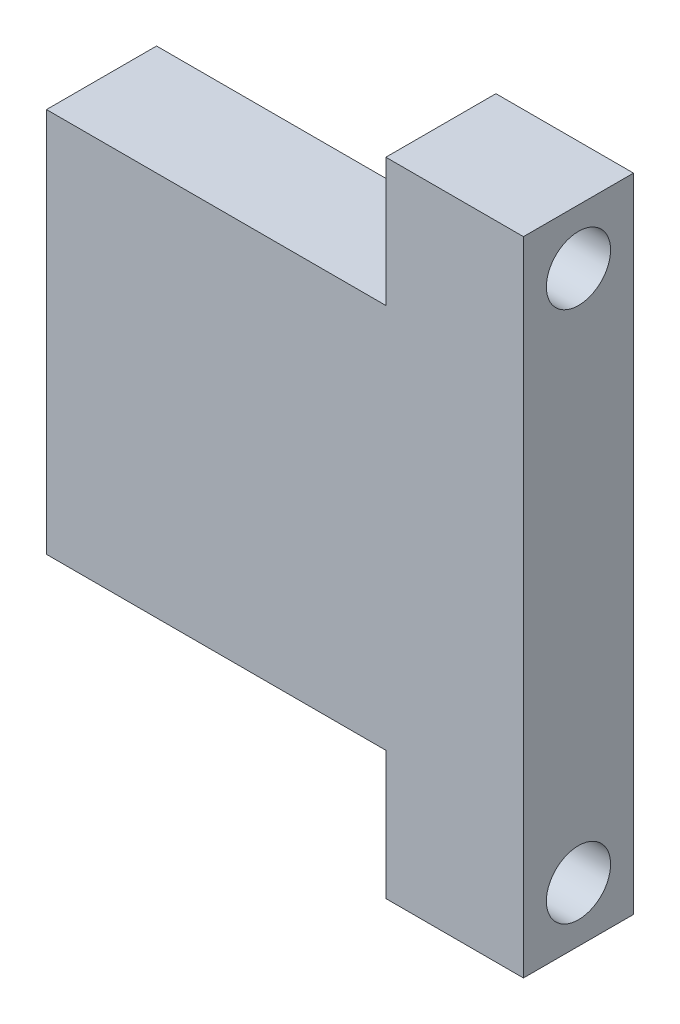
SolidWorks part; units mm, degrees
ref_plane "Front" through (0, 0, 0) normal (0, 0, 1) x (1, 0, 0)
ref_plane "Top" through (0, 0, 0) normal (0, 1, 0) x (1, 0, 0)
ref_plane "Right" through (0, 0, 0) normal (1, 0, 0) x (0, 0, -1)
sketch "Sketch1" plane through (0, 0, 0) normal (0, 0, 1) x (1, 0, 0)
  line L0 (-55.8775, 0) -> (12.9894, 0) construction
  line L1 (0, -35) -> (-52, -35)
  line L2 (0, -35) -> (0, 35)
  line L3 (0, 35) -> (-52, 35)
  line L4 (-52, -35) -> (-52, 35)
  dimension "D1" = 70
  dimension "D2" = 52
extrude "Boss-Extrude1" add sketch "Sketch1" against normal blind 12
sketch "Sketch2" plane through (0, 0, 0) normal (0, 0, 1) x (1, 0, 0)
  line L0 (-60.3695, 0) -> (16.9154, 0) construction
  line L1 (-52, 35) -> (-15, 35)
  line L2 (-52, 35) -> (-52, 21)
  line L3 (-52, 21) -> (-15, 21)
  line L4 (-15, 35) -> (-15, 21)
  line L5 (-52, -35) -> (-15, -35)
  line L6 (-52, -35) -> (-52, -21)
  line L7 (-52, -21) -> (-15, -21)
  line L8 (-15, -35) -> (-15, -21)
  line L9 (0, -35) -> (0, 35) construction
  dimension "D1" = 42
  dimension "D2" = 15
extrude "Cut-Extrude1" cut sketch "Sketch2" against normal through all
hole_wizard "Ø7.0 (7) Diameter Hole1" positions "Sketch4" profile "Sketch3" hole size "Ø7.0" standard "JIS"
sketch "Sketch4" plane through (-15, 0, 0) normal (-1, 0, 0) x (0, 0, 1)
  line L0 (-19.654, 0) -> (5.5038, 0) construction
  line L2 (0, 21) -> (0, 35) construction
  point P0 (-6, 29)
  point P1 (-6, -29)
  dimension "D1" = 6
  dimension "D2" = 58
sketch "Sketch3" plane through (-15, 29, -6) normal (0, 1, 0) x (0, 0, 1)
  line L0 (0, 0) -> (0, 62.103)
  line L1 (0, 62.103) -> (3.5, 60)
  line L2 (3.5, 60) -> (3.5, 0)
  line L5 (3.5, 0) -> (0, 0)
  line L10 (0, 62.103) -> (-3.5, 60) construction
  line L11 (0, -6.35) -> (0, 107.95) construction
  dimension "Hole Dia." = 7
  dimension "Hole Depth" = 60
  dimension "Drill Angle" = 118
hole_wizard "M6x1.0 Tapped Hole1" positions "Sketch6" profile "Sketch5" tap size "M6x1.0" standard "JIS"
sketch "Sketch6" plane through (-52, 0, 0) normal (-1, 0, 0) x (0, 0, 1)
  line L0 (-17.8263, 0) -> (4.6437, 0) construction
  line L2 (0, 21) -> (0, -21) construction
  point P0 (-6, 14)
  point P1 (-6, -14)
  dimension "D1" = 6
  dimension "D2" = 28
sketch "Sketch5" plane through (-52, 14, -6) normal (0, 1, 0) x (0, 0, 1)
  line L0 (0, 0) -> (0, 19.5022)
  line L1 (0, 19.5022) -> (2.5, 18)
  line L2 (2.5, 18) -> (2.5, 0)
  line L5 (2.5, 0) -> (0, 0)
  line L10 (0, 19.5022) -> (-2.5, 18) construction
  line L11 (0, -6.35) -> (0, 107.95) construction
  dimension "Tap Drill Dia." = 5
  dimension "Tap Drill Depth" = 18
  dimension "Drill Angle" = 118
cosmetic thread "Hole Thread1" parameters "D1"=15, "D2"=6
cosmetic thread "Hole Thread2" parameters "D1"=15, "D2"=6
